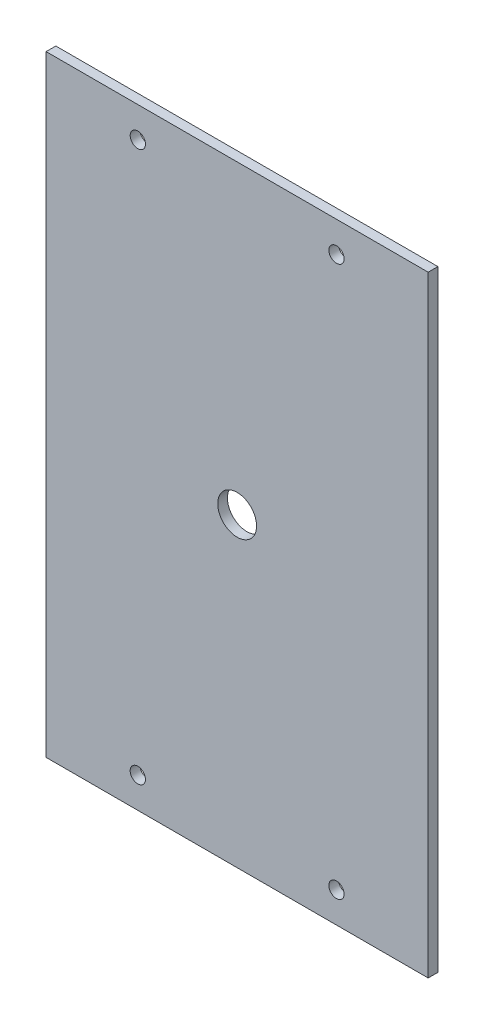
SolidWorks part; units mm, degrees
material "Custom Plastic"
ref_plane "Front Plane" through (0, 0, 0) normal (0, 0, 1) x (1, 0, 0)
ref_plane "Top Plane" through (0, 0, 0) normal (0, 1, 0) x (1, 0, 0)
ref_plane "Right Plane" through (0, 0, 0) normal (1, 0, 0) x (0, 0, -1)
sketch "Sketch1" plane through (0, 0, 0) normal (0, 0, 1) x (1, 0, 0)
  line L1 (-125, 200) -> (0, 200)
  line L2 (-125, 200) -> (-125, 0)
  line L3 (-125, 0) -> (0, 0)
  line L4 (0, 200) -> (0, 0)
  dimension "D1" = 200
  dimension "D2" = 125
extrude "Boss-Extrude1" add sketch "Sketch1" along normal blind 3.175
sketch "Sketch2" plane through (0, 0, 3.175) normal (0, 0, 1) x (1, 0, 0)
  line L0 (-125, 200) -> (-125, 0) construction
  line L1 (0, 0) -> (0, 200) construction
  line L2 (0, 200) -> (-125, 200) construction
  circle A0 centre (-95, 190) radius 2.5
  circle A1 centre (-30, 190) radius 2.5
  dimension "D1" = 5
  dimension "D2" = 5
  dimension "D3" = 30
  dimension "D4" = 30
  dimension "D5" = 10
  dimension "D6" = 10
extrude "Cut-Extrude1" cut sketch "Sketch2" against normal up to surface (3.175 mm away) up to face at (-62.5, 100, 0)
ref_plane "Plane1" through (0, 100, 0) normal (0, 1, 0) x (1, 0, 0)
mirror "Mirror1" about plane through (0, 100, 0) normal (0, 1, 0) of "Cut-Extrude1"
sketch "Sketch3" plane through (0, 0, 3.175) normal (0, 0, 1) x (1, 0, 0)
  line L0 (1.7463, 100) -> (-1.7463, 100) construction
  line L2 (-62.5, 200) -> (-62.5, 0) construction
  line L3 (0, 200) -> (-125, 200) construction
  line L4 (-125, 0) -> (0, 0) construction
  line L5 (-125, 100) -> (0, 100) construction
  line L6 (-125, 200) -> (-125, 0) construction
  line L7 (0, 0) -> (0, 200) construction
  circle A0 centre (-62.5, 100) radius 6.35
  dimension "D1" = 12.7
extrude "Cut-Extrude2" cut sketch "Sketch3" against normal up to surface (3.175 mm away) up to face at (-92.5, 10, 0)
